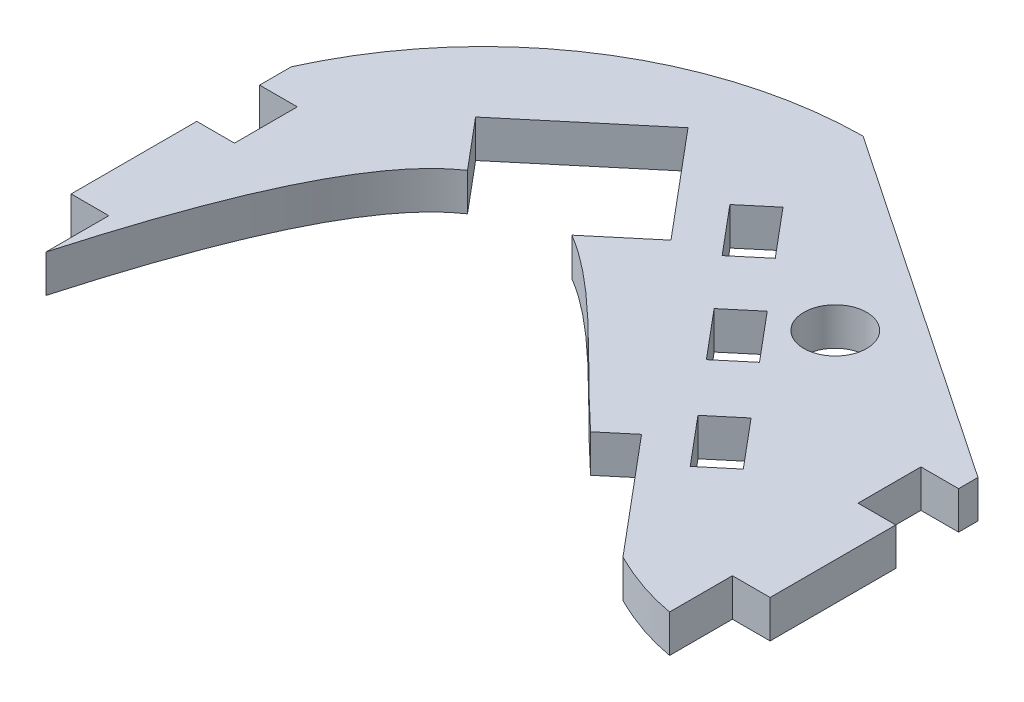
SolidWorks part; units mm, degrees
ref_plane "Alzado" through (0, 0, 0) normal (0, 0, 1) x (1, 0, 0)
ref_plane "Planta" through (0, 0, 0) normal (0, 1, 0) x (1, 0, 0)
ref_plane "Vista lateral" through (0, 0, 0) normal (1, 0, 0) x (0, 0, -1)
sketch "Croquis1" plane through (0, 0, 0) normal (0, 1, 0) x (1, 0, 0)
  circle A0 centre (0, 0) radius 30.5
extrude "Saliente-Extruir1" add sketch "Croquis1" along normal blind 3
sketch "Croquis2" plane through (0, 3, 0) normal (0, 1, 0) x (1, 0, 0)
  circle A0 centre (0, 0) radius 2
extrude "Cortar-Extruir1" cut sketch "Croquis2" against normal blind 4
sketch "Croquis5" plane through (0, 3, 0) normal (0, 1, 0) x (1, 0, 0)
  line L0 (0, 0) -> (0, 10)
  line L1 (28.8141, -5) -> (30.0874, -5)
  line L2 (28.8141, 5) -> (30.0874, 5)
  line L3 (-24.8141, 10) -> (-28.8141, 10)
  line L4 (24.8141, -5) -> (24.8141, -10)
  line L5 (-24.8141, -10) -> (-28.8141, -10)
  line L6 (24.8141, -5) -> (28.8141, -5)
  line L7 (24.8141, 5) -> (24.8141, 10)
  line L8 (-24.8141, 5) -> (-28.8141, 5)
  line L9 (-24.8141, 5) -> (-24.8141, 10)
  line L10 (-24.8141, -5) -> (-28.8141, -5)
  line L11 (-24.8141, -5) -> (-24.8141, -10)
  line L12 (24.8141, 5) -> (28.8141, 5)
  line L13 (24.8141, -10) -> (28.8141, -10)
  line L14 (24.8141, 10) -> (28.8141, 10)
  line L15 (-28.8141, 5) -> (-30.0874, 5)
  line L16 (-28.8141, -5) -> (-30.0874, -5)
  circle A1 centre (0, 0) radius 30.5 construction
  arc A2 (-28.8141, 10) -> (-30.0874, 5) centre (0, 0) ccw
  arc A3 (28.8141, 10) -> (28.8141, -10) centre (0, 0) cw
  arc A4 (-30.0874, -5) -> (-28.8141, -10) centre (0, 0) ccw
  arc A5 (30.0874, -5) -> (28.8141, -10) centre (0, 0) cw
  arc A6 (28.8141, 10) -> (30.0874, 5) centre (0, 0) cw
extrude "Cortar-Extruir3" cut sketch "Croquis5" against normal blind 4
sketch "Croquis7" plane through (0, 3, 0) normal (0, 1, 0) x (1, 0, 0)
  line L0 (-8.1011, 29.1011) -> (9.5756, 8.0348)
  line L1 (-1.4002, 16.4481) -> (-0.7574, 15.682)
  line L2 (-8.1011, 29.1011) -> (-27.2522, 13.0314)
  line L3 (27.2522, -13.0314) -> (8.1011, -29.1011)
  line L4 (8.1011, -29.1011) -> (-27.2522, 13.0314)
  line L5 (1.4284, 22.4114) -> (-0.8697, 20.4831)
  line L6 (1.4284, 22.4114) -> (4.6423, 18.5812)
  line L7 (4.6423, 18.5812) -> (2.3442, 16.6528)
  line L8 (2.3442, 16.6528) -> (-0.8697, 20.4831)
  line L9 (-24.8141, -10) -> (-28.8141, -10)
  line L10 (24.8141, -10) -> (28.8141, -10)
  line L11 (9.5756, 8.0348) -> (18.4139, -2.4983)
  line L12 (18.4139, -2.4983) -> (27.2522, -13.0314)
  line L13 (11.4555, 1.1272) -> (19.169, -8.0653)
  line L14 (19.169, -8.0653) -> (9.9765, -15.7788)
  line L15 (9.9765, -15.7788) -> (2.263, -6.5863)
  line L16 (11.4555, 1.1272) -> (2.263, -6.5863)
  line L17 (-1.4002, 16.4481) -> (-7.8281, 24.1085)
  line L18 (-1.4002, 16.4481) -> (-10.5927, 8.7346)
  line L19 (-10.5927, 8.7346) -> (-17.0206, 16.3951)
  line L20 (-7.8281, 24.1085) -> (-17.0206, 16.3951)
  line L21 (16.2929, 4.6967) -> (14.6859, 6.6118)
  line L22 (16.2929, 4.6967) -> (17.8998, 2.7815)
  line L23 (14.6859, 6.6118) -> (12.3878, 4.6834)
  line L24 (17.8998, 2.7815) -> (15.6017, 0.8532)
  line L25 (15.6017, 0.8532) -> (12.3878, 4.6834)
  line L26 (-0.7574, 15.682) -> (-5.0494, 12.0807)
  arc A1 (-28.8141, -10) -> (28.8141, -10) centre (0, 0) ccw
  spline S0 degree 3 poles (24.8141, -10) (2.6081, -6.0995) (-10.3265, 41.1093) (-24.8141, -10) knots 0 0 0 0 1 1 1 1
  point P7 (-9.5756, -8.0348)
extrude "Cortar-Extruir5" cut sketch "Croquis7" against normal blind 4
sketch "Croquis9" plane through (0, 3, 0) normal (0, 1, 0) x (1, 0, 0)
  line L0 (-8.3073, 29.3469) -> (22.8679, -7.8063)
  line L2 (7.9714, 14.6138) -> (11.1854, 10.7835)
  line L3 (-8.3073, 29.3469) -> (-21.7131, 18.0981)
  line L4 (-21.7131, 18.0981) -> (9.4621, -19.0551)
  line L5 (9.4621, -19.0551) -> (22.8679, -7.8063)
  line L6 (11.1854, 10.7835) -> (8.8872, 8.8552)
  line L7 (7.9714, 14.6138) -> (5.6733, 12.6854)
  arc A1 (28.8141, 10) -> (-28.8141, 10) centre (0, 0) ccw construction
extrude "Cortar-Extruir6" cut sketch "Croquis9" against normal blind 10 contours L2 L7 L0 L6
sketch "Croquis10" plane through (0, 3, 0) normal (0, 1, 0) x (1, 0, 0)
  line L0 (0, 0) -> (12, 0)
  line L1 (12, 0) -> (12, 16)
  circle A0 centre (12, 16) radius 2.5
extrude "Cortar-Extruir7" cut sketch "Croquis10" against normal blind 3
sketch "Croquis11" plane through (0, 3, 0) normal (0, 1, 0) x (1, 0, 0)
  line L0 (-24.8141, 10) -> (-27.8141, 10)
  line L1 (-24.8141, 10) -> (-28.8141, 10) construction
  line L2 (-27.8141, 10) -> (-27.8141, 12.5151)
  line L3 (-24.8141, 5) -> (-27.8141, 5)
  line L4 (-24.8141, 5) -> (-30.0874, 5) construction
  line L5 (-27.8141, 5) -> (-27.8141, -5)
  line L6 (-24.8141, -5) -> (-30.0874, -5) construction
  line L7 (24.8141, 10) -> (27.8141, 10)
  line L8 (24.8141, 10) -> (28.8141, 10) construction
  line L9 (27.8141, 10) -> (27.8141, 12.5151)
  line L10 (24.8141, 5) -> (27.8141, 5)
  line L11 (24.8141, 5) -> (30.0874, 5) construction
  line L12 (27.8141, 5) -> (27.8141, -5)
  line L13 (24.8141, -5) -> (30.0874, -5) construction
  arc A0 (28.8141, 10) -> (-28.8141, 10) centre (0, 0) ccw construction
  line M20 (24.8141, -5) -> (30.0874, -5)
  arc M21 (30.0874, -5) -> (30.0874, 5) centre (0, 0) ccw
  line M22 (30.0874, 5) -> (24.8141, 5)
  line M24 (24.8141, 10) -> (28.8141, 10)
  arc M25 (28.8141, 10) -> (-28.8141, 10) centre (0, 0) ccw
  line M26 (-28.8141, 10) -> (-24.8141, 10)
  line M28 (-24.8141, 5) -> (-30.0874, 5)
  arc M29 (-30.0874, 5) -> (-30.0874, -5) centre (0, 0) ccw
  line M30 (-30.0874, -5) -> (-24.8141, -5)
extrude "Cortar-Extruir8" cut sketch "Croquis11" against normal through all and the other way through all contours L12 M22 M20 M21 | L9 M24 M25 | L5 M28 M29 M30 | L2 M26 M25
sketch "Croquis12" plane through (0, 3, 0) normal (0, 1, 0) x (1, 0, 0)
  line L3 (29.8013, 10.2046) -> (-1.7022, 31.454)
  circle A0 centre (0, 0) radius 31.5
  line M23 (27.8141, 10) -> (27.8141, 12.5151)
  arc M24 (27.8141, 12.5151) -> (-27.8141, 12.5151) centre (0, 0) ccw
extrude "Cortar-Extruir9" cut sketch "Croquis12" against normal blind 10 contours L3 M23 M24
